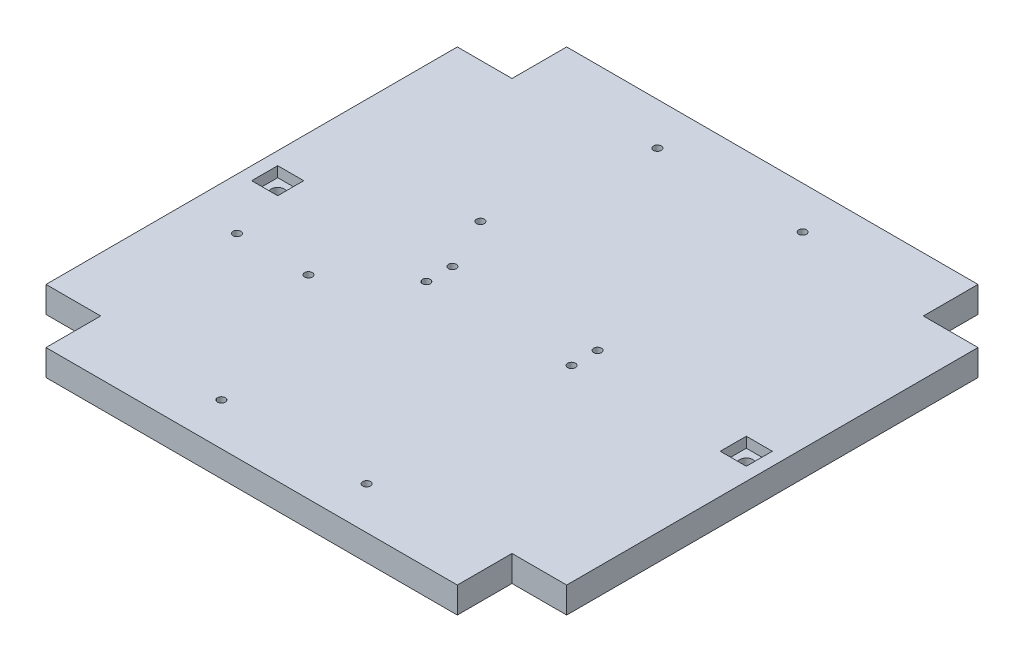
SolidWorks part; units mm, degrees
ref_plane "Front Plane" through (0, 0, 0) normal (0, 0, 1) x (1, 0, 0)
ref_plane "Top Plane" through (0, 0, 0) normal (0, 1, 0) x (1, 0, 0)
ref_plane "Right Plane" through (0, 0, 0) normal (1, 0, 0) x (0, 0, -1)
sketch "Sketch1" plane through (0, 0, 0) normal (0, 1, 0) x (1, 0, 0)
  line L0 (-79, 100) -> (-79, 79)
  line L1 (-79, -100) -> (79, -100)
  line L2 (-100, -79) -> (-100, 79)
  line L3 (-79, 100) -> (79, 100)
  line L4 (100, -79) -> (100, 79)
  line L5 (-79, -79) -> (79, 79) construction
  line L6 (-79, 79) -> (79, -79) construction
  line L7 (-79, 79) -> (-100, 79)
  line L9 (0, 100) -> (0, -100) construction
  line L10 (-100, 0) -> (100, 0) construction
  line L11 (79, 79) -> (100, 79)
  line L12 (79, 100) -> (79, 79)
  line L13 (79, -79) -> (100, -79)
  line L14 (79, -100) -> (79, -79)
  line L15 (-79, -100) -> (-79, -79)
  line L16 (-79, -79) -> (-100, -79)
  point P0 (0, 0)
  dimension "D3" = 21
  dimension "D4" = 21
extrude "Boss-Extrude1" add sketch "Sketch1" along normal blind 10
sketch "Sketch2" plane through (0, 10, 0) normal (0, 1, 0) x (1, 0, 0)
  line L0 (0, 100) -> (0, 90) construction
  line L1 (79, 100) -> (-79, 100) construction
  line L2 (-100, 0) -> (-90, 0) construction
  line L3 (-100, 79) -> (-100, -79) construction
  line L4 (0, 0) -> (0, 24.4483) construction
  line L5 (0, 0) -> (-27.2042, 0) construction
  circle A1 centre (-90, 0) radius 2.5
  circle A2 centre (90, 0) radius 2.5
  dimension "D4" = 5
  dimension "D1" = 10
  dimension "D3" = 10
extrude "Cut-Extrude1" cut sketch "Sketch2" against normal blind 10
sketch "Sketch3" plane through (0, 10, 0) normal (0, 1, 0) x (1, 0, 0)
  line L0 (0, 5) -> (0, 83.74) construction
  line L1 (0, 83.74) -> (27.9, 83.74) construction
  line L2 (0, 5) -> (27.9, 5) construction
  line L3 (0, 0) -> (52.9385, 0) construction
  circle A0 centre (27.9, 83.74) radius 1.5
  circle A1 centre (27.9, 5) radius 1.5
  circle A2 centre (-27.9, 5) radius 1.5
  circle A3 centre (-27.9, 83.74) radius 1.5
  circle A4 centre (-27.9, -5) radius 1.5
  circle A5 centre (27.9, -5) radius 1.5
  circle A6 centre (27.9, -83.74) radius 1.5
  circle A7 centre (-27.9, -83.74) radius 1.5
  dimension "D4" = 3
  dimension "D5" = 3
  dimension "D1" = 5
  dimension "D2" = 78.74
  dimension "D3" = 27.9
extrude "Cut-Extrude2" cut sketch "Sketch3" against normal blind 10
sketch "Sketch6" plane through (0, 10, 0) normal (0, 1, 0) x (1, 0, 0)
  line L0 (0, 0) -> (-35, 0) construction
  line L1 (-35, 0) -> (-37.54, 0) construction
  line L2 (-37.54, 0) -> (-37.54, 25.4) construction
  line L3 (-37.54, 25.4) -> (-37.54, -25.4) construction
  line L4 (-37.54, -25.4) -> (-52.78, -25.4) construction
  line L5 (-52.78, -25.4) -> (-80.27, -25.4) construction
  circle A0 centre (-37.54, 25.4) radius 1.5
  circle A1 centre (-52.78, -25.4) radius 1.5
  circle A2 centre (-80.27, -25.4) radius 1.5
  dimension "D4" = 3
  dimension "D7" = 3
  dimension "D9" = 3
  dimension "D1" = 35
  dimension "D2" = 2.54
  dimension "D3" = 25.4
  dimension "D5" = 50.8
  dimension "D6" = 15.24
  dimension "D8" = 27.49
extrude "Cut-Extrude3" cut sketch "Sketch6" against normal blind 10
sketch "Sketch7" plane through (0, 10, 0) normal (0, 1, 0) x (1, 0, 0)
  line L1 (-95, -5) -> (-85, -5)
  line L2 (-95, -5) -> (-95, 5)
  line L3 (-95, 5) -> (-85, 5)
  line L4 (-85, -5) -> (-85, 5)
  line L5 (-95, -5) -> (-85, 5) construction
  line L6 (-95, 5) -> (-85, -5) construction
  line L7 (95, -5) -> (85, -5)
  line L8 (95, -5) -> (95, 5)
  line L9 (95, 5) -> (85, 5)
  line L10 (85, -5) -> (85, 5)
  line L11 (95, -5) -> (85, 5) construction
  line L12 (95, 5) -> (85, -5) construction
  point P0 (-90, 0)
  point P6 (90, 0)
  dimension "D1" = 10
  dimension "D2" = 10
  dimension "D3" = 10
  dimension "D4" = 10
extrude "Cut-Extrude4" cut sketch "Sketch7" against normal blind 4
